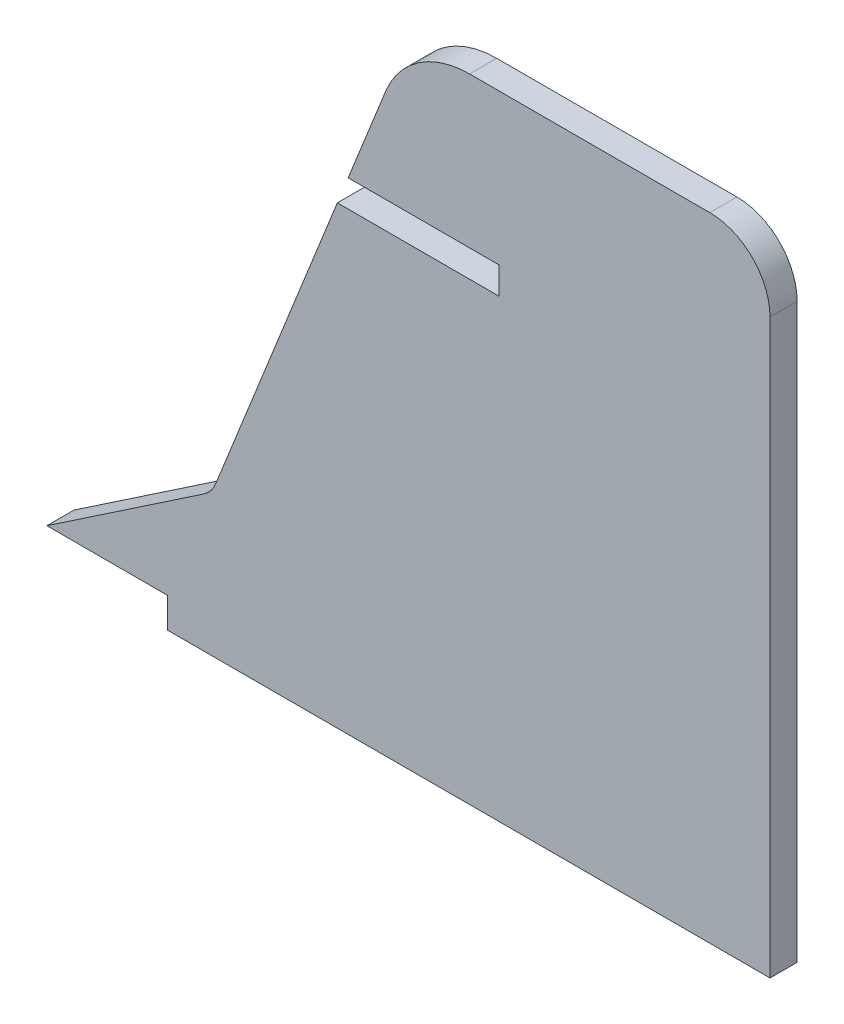
SolidWorks part; units mm, degrees
material "Balsa"
ref_plane "Front" through (0, 0, 0) normal (0, 0, 1) x (1, 0, 0)
ref_plane "Top" through (0, 0, 0) normal (0, 1, 0) x (1, 0, 0)
ref_plane "Right" through (0, 0, 0) normal (1, 0, 0) x (0, 0, -1)
sketch "Sketch1" plane through (0, 0, 0) normal (0, 0, 1) x (1, 0, 0)
  line L0 (7.4, 18.5) -> (28.2, 70.5)
  line L1 (40, 100) -> (100, 100)
  line L2 (100, 100) -> (100, 0)
  line L4 (100, 0) -> (100, -5)
  line L5 (100, -5) -> (0, -5)
  line L6 (0, -5) -> (0, 0)
  line L7 (0, 0) -> (-20, 0)
  line L8 (-20, 0) -> (7.4, 18.5)
  line L9 (30, 75) -> (55, 75)
  line L10 (55, 75) -> (55, 70.5)
  line L11 (55, 70.5) -> (28.2, 70.5)
  line L12 (30, 75) -> (40, 100)
  dimension "D1" = 100
  dimension "D2" = 100
  dimension "D3" = 60
  dimension "D4" = 5
  dimension "D5" = 20
  dimension "D6" = 18.5
  dimension "D7" = 4.5
  dimension "D8" = 25
  dimension "D9" = 25
extrude "Boss-Extrude1" add sketch "Sketch1" along normal blind 4.5
fillet "Fillet1" radius 5 1 edges at (7.4, 18.5, 2.25)
fillet "Fillet2" radius 10 1 edges at (100, 100, 2.25)
fillet "Fillet3" radius 15 1 edges at (40, 100, 2.25)
